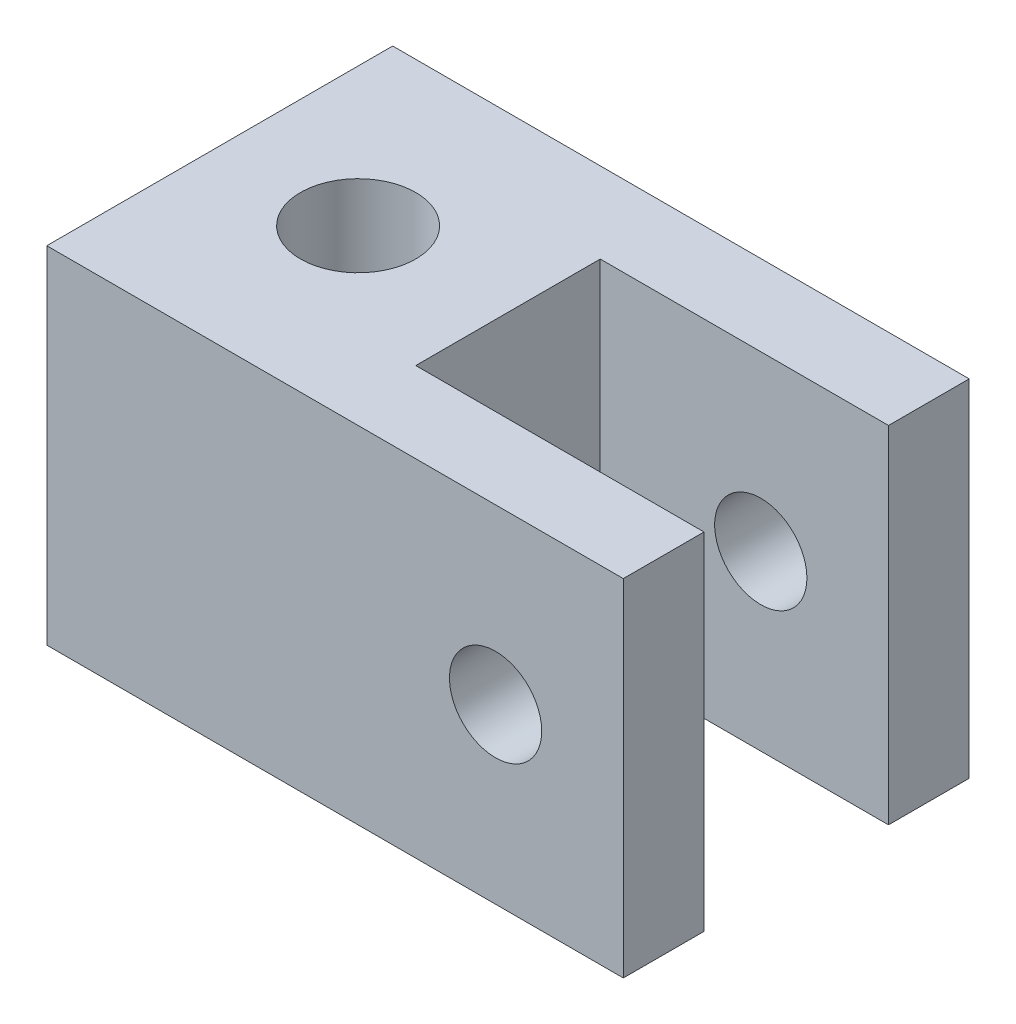
SolidWorks part; units mm, degrees
ref_plane "Alzado" through (0, 0, 0) normal (0, 0, 1) x (1, 0, 0)
ref_plane "Planta" through (0, 0, 0) normal (0, 1, 0) x (1, 0, 0)
ref_plane "Vista lateral" through (0, 0, 0) normal (1, 0, 0) x (0, 0, -1)
sketch "Croquis1" plane through (0, 0, 0) normal (1, 0, 0) x (0, 0, -1)
  line L1 (7.5, -7.5) -> (-7.5, -7.5)
  line L2 (7.5, -7.5) -> (7.5, 7.5)
  line L3 (7.5, 7.5) -> (-7.5, 7.5)
  line L4 (-7.5, -7.5) -> (-7.5, 7.5)
  line L5 (7.5, -7.5) -> (-7.5, 7.5) construction
  line L6 (7.5, 7.5) -> (-7.5, -7.5) construction
  point P0 (0, 0)
  point P6 (-7.5, 0)
  point P7 (7.5, 0)
  dimension "D1" = 15
  dimension "D2" = 15
extrude "Saliente-Extruir1" add sketch "Croquis1" along normal mid plane 25
sketch "Croquis2" plane through (0, 7.5, 0) normal (0, 1, 0) x (1, 0, 0)
  line L0 (-12.5, 7.5) -> (-12.5, -7.5) construction
  line L1 (12.5, 7.5) -> (12.5, -7.5) construction
  line L2 (0, -4) -> (25, -4)
  line L3 (0, -4) -> (0, 4)
  line L4 (0, 4) -> (25, 4)
  line L5 (25, -4) -> (25, 4)
  line L6 (0, -4) -> (25, 4) construction
  line L7 (0, 4) -> (25, -4) construction
  circle A0 centre (-6.5, 0) radius 2.5
  point P4 (12.5, 0)
  dimension "D1" = 5
  dimension "D2" = 6
  dimension "D3" = 8
  dimension "D4" = 25
extrude "Cortar-Extruir1" cut sketch "Croquis2" against normal through all
sketch "Croquis3" plane through (0, 0, 7.5) normal (0, 0, 1) x (1, 0, 0)
  circle A0 centre (6.9615, 0) radius 2
extrude "Cortar-Extruir2" cut sketch "Croquis3" against normal through all
